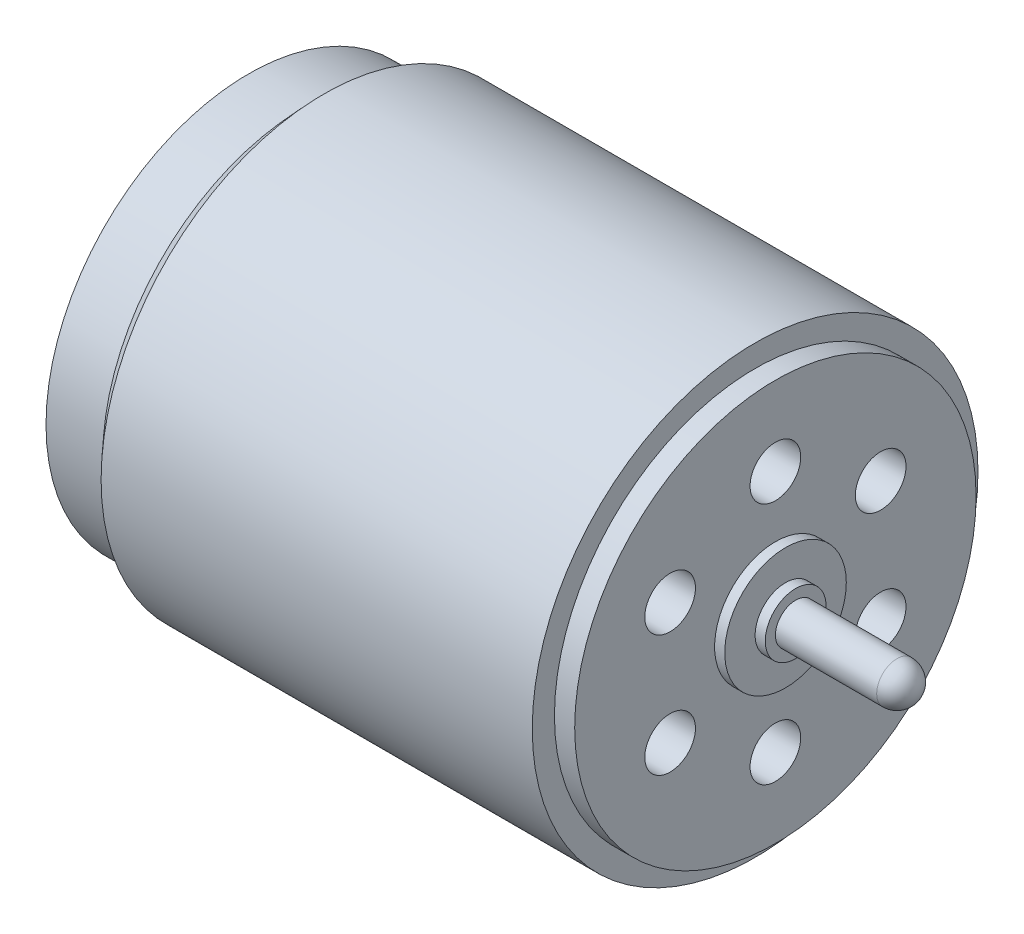
SolidWorks part; units mm, degrees
ref_plane "Alzado" through (0, 0, 0) normal (0, 0, 1) x (1, 0, 0)
ref_plane "Planta" through (0, 0, 0) normal (0, 1, 0) x (1, 0, 0)
ref_plane "Vista lateral" through (0, 0, 0) normal (1, 0, 0) x (0, 0, -1)
sketch "Croquis4" plane through (0, 0, 0) normal (1, 0, 0) x (0, 0, -1)
  circle A0 centre (0, 0) radius 11
  dimension "D1" = 22
extrude "Saliente-Extruir2" add sketch "Croquis4" along normal blind 25
sketch "Croquis5" plane through (25, 0, 0) normal (1, 0, 0) x (0, 0, -1)
  circle A0 centre (0, 0) radius 3
  dimension "D1" = 6
extrude "Saliente-Extruir3" add sketch "Croquis5" along normal blind 1.5
sketch "Croquis6" plane through (26.5, 0, 0) normal (1, 0, 0) x (0, 0, -1)
  circle A0 centre (0, 0) radius 1.5
  dimension "D1" = 3
extrude "Saliente-Extruir4" add sketch "Croquis6" along normal blind 0.5
sketch "Croquis7" plane through (27, 0, 0) normal (1, 0, 0) x (0, 0, -1)
  circle A0 centre (0, 0) radius 1
  dimension "D1" = 2
extrude "Saliente-Extruir5" add sketch "Croquis7" along normal blind 6
fillet "Redondeo1" radius 1 1 edges at (33, 0, -1)
sketch "Croquis10" plane through (25, 0, 0) normal (1, 0, 0) x (0, 0, -1)
  circle A0 centre (0, 0) radius 9.9059
extrude "Saliente-Extruir6" add sketch "Croquis10" along normal blind 1
sketch "Croquis9" plane through (0, 0, 0) normal (0, 0, 1) x (1, 0, 0)
  line L0 (3.7194, 11) -> (2.7987, 10)
  line L1 (25, 11) -> (0, 11) construction
  line L2 (2.7987, 10) -> (0, 10)
  line L3 (0, 11) -> (0, -11) construction
  line L4 (0, 10) -> (0, -10)
  line L5 (0, 0) -> (2.6073, 0) construction
  line L6 (3.7194, 11) -> (0, 11)
  line L7 (0, 11) -> (0, 10)
  line L8 (0, -11) -> (0, -10)
  line L9 (2.7987, -10) -> (0, -10)
  line L10 (3.7194, -11) -> (2.7987, -10)
  line L11 (3.7194, -11) -> (0, -11)
  point P11 (0, 0)
  dimension "D1" = 20
revolve "Cortar-Revolución2" cut sketch "Croquis9" angle 360 about L5
sketch "Croquis8" plane through (25, 0, 0) normal (1, 0, 0) x (0, 0, -1)
  circle A0 centre (0, 0) radius 6
  circle A1 centre (0, 6) radius 1.25
  circle A2 centre (5.1962, 3) radius 1.25
  circle A3 centre (5.1962, -3) radius 1.25
  circle A4 centre (0, -6) radius 1.25
  circle A5 centre (-5.1962, -3) radius 1.25
  circle A6 centre (-5.1962, 3) radius 1.25
  dimension "D1" = 12
  dimension "D2" = 2.5
  dimension "D3" = 6
extrude "Cortar-Extruir1" cut sketch "Croquis8" against normal blind 6 from surface at 1 contours A0 A6 | A0 A6 | A0 A1 | A0 A1 | A0 A2 | A0 A2 | A0 A3 | A0 A3 | A0 A4 | A0 A4 | A0 A5 | A0 A5
equation "\"6mmmm\"=1.5"
